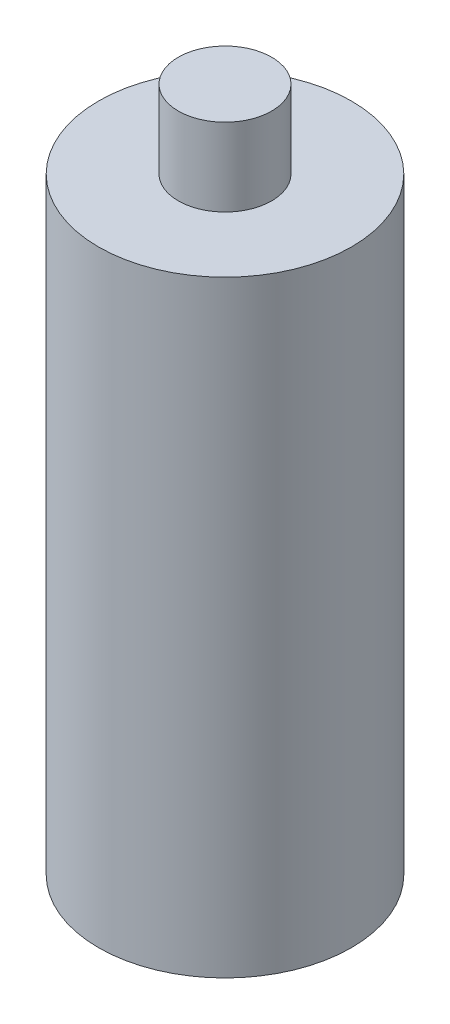
SolidWorks part; units mm, degrees
material "1.4122 (X39CrMo17-1)"
ref_plane "前视基准面" through (0, 0, 0) normal (0, 0, 1) x (1, 0, 0)
ref_plane "上视基准面" through (0, 0, 0) normal (0, 1, 0) x (1, 0, 0)
ref_plane "右视基准面" through (0, 0, 0) normal (1, 0, 0) x (0, 0, -1)
other "Configuration Table"
sketch "草图1" plane through (0, 0, 0) normal (0, 1, 0) x (1, 0, 0)
  circle A0 centre (0, 0) radius 3.25
  dimension "D1" = 6.5
extrude "凸台-拉伸1" add sketch "草图1" along normal blind 15.6 contours A0
sketch "草图2" plane through (0, 15.6, 0) normal (0, 1, 0) x (1, 0, 0)
  circle A0 centre (0, 0) radius 1.2
  dimension "D1" = 2.4
extrude "凸台-拉伸2" add sketch "草图2" along normal blind 2
